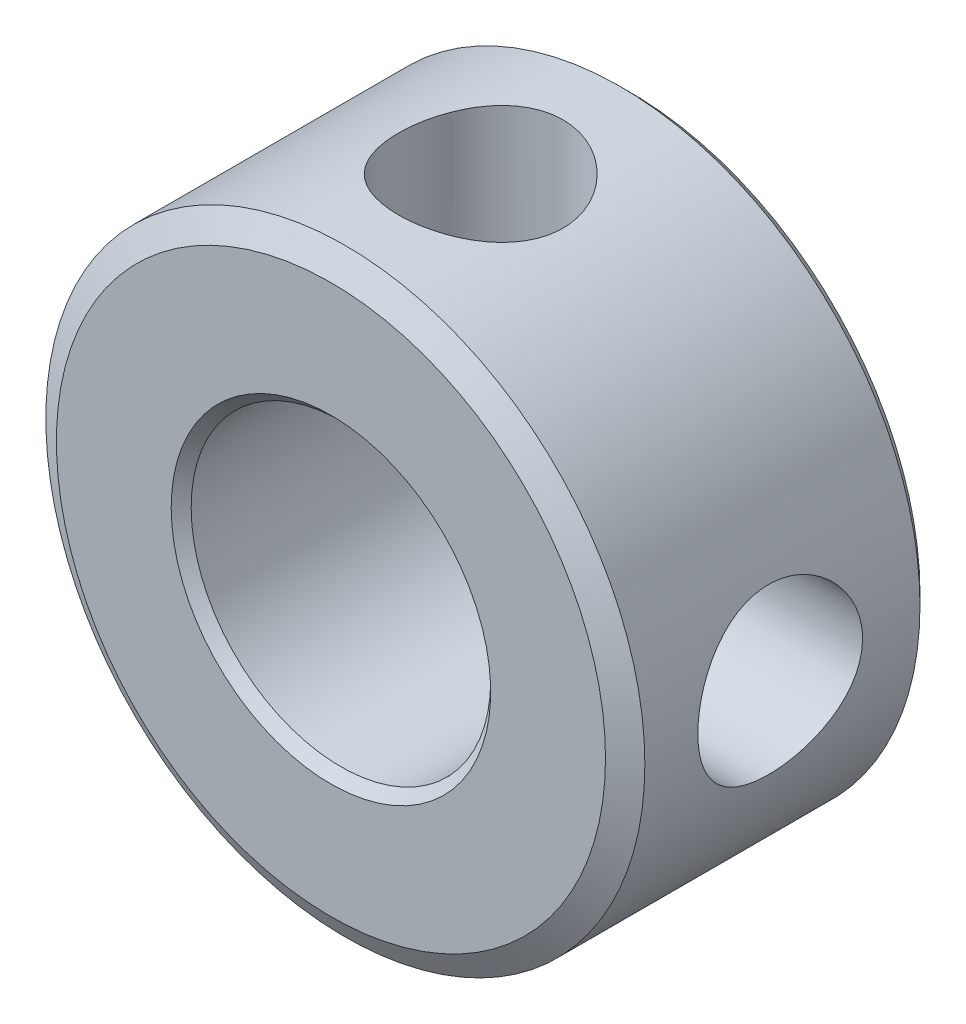
SolidWorks part; units mm, degrees
material "S45C"
ref_plane "Front Plane" through (0, 0, 0) normal (0, 0, 1) x (1, 0, 0)
ref_plane "Top Plane" through (0, 0, 0) normal (0, 1, 0) x (1, 0, 0)
ref_plane "Right Plane" through (0, 0, 0) normal (1, 0, 0) x (0, 0, -1)
sketch "Sketch1" plane through (0, 0, 0) normal (1, 0, 0) x (0, 0, -1)
  line L0 (0, 0) -> (6, 0) construction
  line L1 (0, 6) -> (6, 6)
  line L3 (0, 3) -> (6, 3)
  line L4 (6, 6) -> (6, 3)
  line L5 (0, 3) -> (0, 6)
  dimension "D" = 6
  dimension "D1." = 12
  dimension "B" = 6
revolve "Revolve1" add sketch "Sketch1" angle 360 about L0
ref_plane "Plane1" through (0, 6, 0) normal (0, 1, 0) x (1, 0, 0)
hole_wizard "Tapped Hole1" positions "Sketch3" profile "Sketch2" tap size "M4x0.7" standard "JIS"
sketch "Sketch3" plane through (0, 6, 0) normal (0, 1, 0) x (1, 0, 0)
  line L2 (6, 6) -> (-6, 6) construction
  point P0 (0, 3)
sketch "Sketch2" plane through (0, 6, -3) normal (1, 0, 0) x (0, 0, 1)
  line L0 (0, 0) -> (0, 3)
  line L1 (0, 3) -> (1.65, 3)
  line L2 (1.65, 3) -> (1.65, 0)
  line L5 (1.65, 0) -> (0, 0)
  line L11 (0, 0) -> (0, 3) construction
  dimension "Thru Tap Drill Dia." = 3.3
  dimension "Thru Tap Drill Depth" = 3
cosmetic thread "Hole Thread2" parameters "M"=4
pattern_circular "CirPattern1" count 2 every 90 about axis through (0, 0, 0) along (0, 0, 1) of "Tapped Hole1"
chamfer "Chamfer1" distance 0.2 3 edges at (6, 0, -6) (3, 0, 0) (3, 0, -6)
sketch "Sketch4" plane through (0, 0, 0) normal (1, 0, 0) x (0, 0, -1)
  line L1 (0.2887, 6) -> (0, 5.5)
  line L3 (0, 6) -> (6, 6) construction
  line L4 (0.2887, 6) -> (0, 6)
  line L5 (0, 0) -> (6, 0) construction
  line L6 (6, -6) -> (6, 6) construction
  line L7 (0, 3) -> (0, 6) construction
  line L8 (0, 6) -> (0, 5.5)
  dimension "D1_s" = 11
  dimension "D1" = 30
revolve "Cut-Revolve1" cut sketch "Sketch4" angle 360 about L5
sketch "Sketch5" [suppressed] plane through (0, 0, 0) normal (1, 0, 0) x (0, 0, -1)
  line L0 (0, 5.5) -> (0, 5)
  line L1 (0, 5.5) -> (0, -5.5) construction
  line L2 (0, 5) -> (0.2887, 5.5)
  line L5 (0, 0) -> (8, 0) construction
  line L6 (8, -5.3) -> (8, 5.3) construction
  line L7 (0.2887, 5.5) -> (0, 5.5)
  dimension "D1" = 30
  dimension "D1_s" = 11
  dimension "D1." = 12
revolve "Cut-Revolve2" [suppressed] cut sketch "Sketch5" angle 360 about L5
equation "\"D1@Sketch3\"= \"B@Sketch1\" / 2"
equation "\"Cut-Revolve1\" = if ( \"D1.@Sketch1\" = \"D1_s@Sketch4\" , \"suppressed\" , \"unsuppressed\" )"
equation "\"Plane dim\"= \"D1.@Sketch1\" * 0.5"
